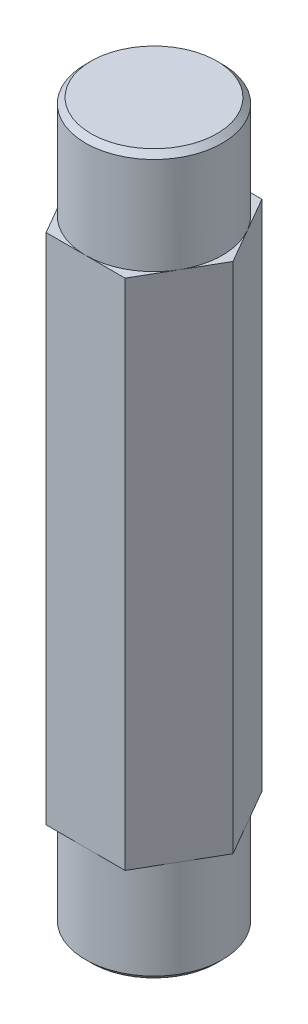
SolidWorks part; units mm, degrees
ref_plane "Front Plane" through (0, 0, 0) normal (0, 0, 1) x (1, 0, 0)
ref_plane "Top Plane" through (0, 0, 0) normal (0, 1, 0) x (1, 0, 0)
ref_plane "Right Plane" through (0, 0, 0) normal (1, 0, 0) x (0, 0, -1)
sketch "Sketch1" plane through (0, 0, 0) normal (0, 1, 0) x (1, 0, 0)
  line L1 (3.6662, -6.35) -> (7.3323, 0)
  line L2 (7.3323, 0) -> (3.6662, 6.35)
  line L3 (3.6662, 6.35) -> (-3.6662, 6.35)
  line L4 (-3.6662, 6.35) -> (-7.3323, 0)
  line L5 (-7.3323, 0) -> (-3.6662, -6.35)
  line L6 (-3.6662, -6.35) -> (3.6662, -6.35)
  circle A0 centre (0, 0) radius 6.35 construction
  dimension "D1" = 12.7
extrude "Boss-Extrude1" add sketch "Sketch1" along normal blind 47.625
sketch "Sketch2" plane through (0, 0, 0) normal (0, -1, 0) x (-1, 0, 0)
  circle A0 centre (0, 0) radius 6.35
  dimension "D1" = 12.7
extrude "Boss-Extrude2" add sketch "Sketch2" along normal blind 9.525
sketch "Sketch3" plane through (0, 47.625, 0) normal (0, 1, 0) x (1, 0, 0)
  circle A0 centre (0, 0) radius 6.35
  dimension "D1" = 12.7
extrude "Boss-Extrude3" add sketch "Sketch3" along normal blind 9.525
chamfer "Chamfer2" distance 0.508 angle 45 2 edges at (0, 57.15, 6.35) (0, -9.525, -6.35)
